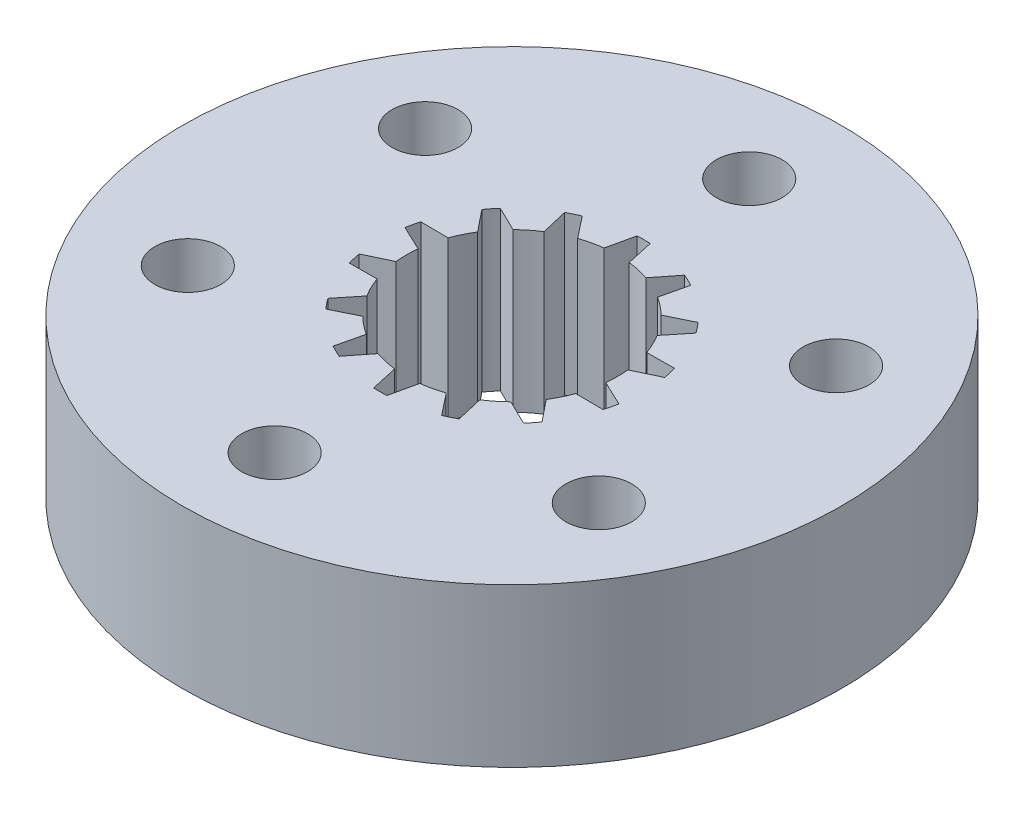
SolidWorks part; units mm, degrees
material "AISI 4340 Steel, normalized"
ref_plane "Front Plane" through (0, 0, 0) normal (0, 0, 1) x (1, 0, 0)
ref_plane "Top Plane" through (0, 0, 0) normal (0, 1, 0) x (1, 0, 0)
ref_plane "Right Plane" through (0, 0, 0) normal (1, 0, 0) x (0, 0, -1)
sketch "Sketch1" plane through (0, 0, 0) normal (0, 1, 0) x (1, 0, 0)
  line L0 (0, -0.0719) -> (0, 49999.9281) construction
  line L1 (0.1282, 0) -> (50000.1282, 0) construction
  line L30 (0, 0.0981) -> (0, 50000.0981) construction
  line L31 (-0.1076, 0) -> (49999.8924, 0) construction
  line L32 (-0.25, 4.9937) -> (-0.4766, 3.9715)
  line L33 (0.25, 4.9937) -> (0.4766, 3.9715)
  line L34 (2.3919, 4.3907) -> (2.1526, 3.3714)
  line L35 (1.9415, 4.6077) -> (1.2937, 3.785)
  line L36 (4.0601, 2.9181) -> (3.4022, 2.1035)
  line L37 (3.7484, 3.309) -> (2.8079, 2.8488)
  line L38 (4.9242, 0.8675) -> (3.978, 0.4191)
  line L39 (4.8129, 1.3549) -> (3.7659, 1.3484)
  line L40 (4.8129, -1.3549) -> (3.7659, -1.3484)
  line L41 (4.9242, -0.8675) -> (3.978, -0.4191)
  line L42 (3.7484, -3.309) -> (2.8079, -2.8488)
  line L43 (4.0601, -2.9181) -> (3.4022, -2.1035)
  line L44 (1.9415, -4.6077) -> (1.2937, -3.785)
  line L45 (2.3919, -4.3907) -> (2.1526, -3.3714)
  line L46 (-0.25, -4.9937) -> (-0.4766, -3.9715)
  line L47 (0.25, -4.9937) -> (0.4766, -3.9715)
  line L48 (-2.3919, -4.3907) -> (-2.1526, -3.3714)
  line L49 (-1.9415, -4.6077) -> (-1.2937, -3.785)
  line L50 (-4.0601, -2.9181) -> (-3.4022, -2.1035)
  line L51 (-3.7484, -3.309) -> (-2.8079, -2.8488)
  line L52 (-4.9242, -0.8675) -> (-3.978, -0.4191)
  line L53 (-4.8129, -1.3549) -> (-3.7659, -1.3484)
  line L54 (-4.8129, 1.3549) -> (-3.7659, 1.3484)
  line L55 (-4.9242, 0.8675) -> (-3.978, 0.4191)
  line L56 (-3.7484, 3.309) -> (-2.8079, 2.8488)
  line L57 (-4.0601, 2.9181) -> (-3.4022, 2.1035)
  line L58 (-1.9415, 4.6077) -> (-1.2937, 3.785)
  line L59 (-2.3919, 4.3907) -> (-2.1526, 3.3714)
  circle A0 centre (0, 0) radius 10 construction
  circle A1 centre (0, 0) radius 12.5
  circle A32 centre (0, 0) radius 4.5 construction
  arc A33 (-0.4766, 3.9715) -> (-1.2937, 3.785) centre (0, 0) ccw
  arc A34 (0.25, 4.9937) -> (-0.25, 4.9937) centre (0, 0) ccw
  arc A35 (2.3919, 4.3907) -> (1.9415, 4.6077) centre (0, 0) ccw
  arc A36 (4.0601, 2.9181) -> (3.7484, 3.309) centre (0, 0) ccw
  arc A37 (4.9242, 0.8675) -> (4.8129, 1.3549) centre (0, 0) ccw
  arc A38 (4.8129, -1.3549) -> (4.9242, -0.8675) centre (0, 0) ccw
  arc A39 (3.7484, -3.309) -> (4.0601, -2.9181) centre (0, 0) ccw
  arc A40 (1.9415, -4.6077) -> (2.3919, -4.3907) centre (0, 0) ccw
  arc A41 (-0.25, -4.9937) -> (0.25, -4.9937) centre (0, 0) ccw
  arc A42 (-2.3919, -4.3907) -> (-1.9415, -4.6077) centre (0, 0) ccw
  arc A43 (-4.0601, -2.9181) -> (-3.7484, -3.309) centre (0, 0) ccw
  arc A44 (-4.9242, -0.8675) -> (-4.8129, -1.3549) centre (0, 0) ccw
  arc A45 (-4.8129, 1.3549) -> (-4.9242, 0.8675) centre (0, 0) ccw
  arc A46 (-3.7484, 3.309) -> (-4.0601, 2.9181) centre (0, 0) ccw
  arc A47 (-1.9415, 4.6077) -> (-2.3919, 4.3907) centre (0, 0) ccw
  arc A48 (1.2937, 3.785) -> (0.4766, 3.9715) centre (0, 0) ccw
  arc A49 (2.8079, 2.8488) -> (2.1526, 3.3714) centre (0, 0) ccw
  arc A50 (-2.1526, 3.3714) -> (-2.8079, 2.8488) centre (0, 0) ccw
  arc A51 (-3.4022, 2.1035) -> (-3.7659, 1.3484) centre (0, 0) ccw
  arc A52 (-3.978, 0.4191) -> (-3.978, -0.4191) centre (0, 0) ccw
  arc A53 (-3.7659, -1.3484) -> (-3.4022, -2.1035) centre (0, 0) ccw
  arc A54 (-2.8079, -2.8488) -> (-2.1526, -3.3714) centre (0, 0) ccw
  arc A55 (-1.2937, -3.785) -> (-0.4766, -3.9715) centre (0, 0) ccw
  arc A56 (0.4766, -3.9715) -> (1.2937, -3.785) centre (0, 0) ccw
  arc A57 (2.1526, -3.3714) -> (2.8079, -2.8488) centre (0, 0) ccw
  arc A58 (3.4022, -2.1035) -> (3.7659, -1.3484) centre (0, 0) ccw
  arc A59 (3.978, -0.4191) -> (3.978, 0.4191) centre (0, 0) ccw
  arc A60 (3.7659, 1.3484) -> (3.4022, 2.1035) centre (0, 0) ccw
  point P85 (0, 0)
  dimension "D1" = 20
  dimension "D2" = 25
  dimension "D3" = 8
  dimension "D4" = 9
  dimension "D5" = 10
  dimension "D7" = 0.5
  dimension "D6" = 25
extrude "Boss-Extrude1" add sketch "Sketch1" along normal blind 6
hole_wizard "M3 Tapped Hole1" positions "Sketch2" profile "Sketch3" tap size "M3" standard "ISO" end condition through all
sketch "Sketch2" plane through (0, 6, 0) normal (0, 1, 0) x (1, 0, 0)
  circle A0 centre (0, 0) radius 9 construction
  point P0 (0, 9)
  point P14 (7.7942, 4.5)
  point P15 (7.7942, -4.5)
  point P16 (0, -9)
  point P17 (-7.7942, -4.5)
  point P18 (-7.7942, 4.5)
  dimension "D1" = 18
  dimension "D2" = 6
sketch "Sketch3" plane through (0, 6, -9) normal (1, 0, 0) x (0, 0, 1)
  line L0 (0, 0) -> (0, 6)
  line L1 (0, 6) -> (1.25, 6)
  line L2 (1.25, 6) -> (1.25, 0)
  line L5 (1.25, 0) -> (0, 0)
  line L11 (0, -6.35) -> (0, 107.95) construction
  dimension "Thru Tap Drill Dia." = 2.5
  dimension "Thru Tap Drill Depth" = 6
